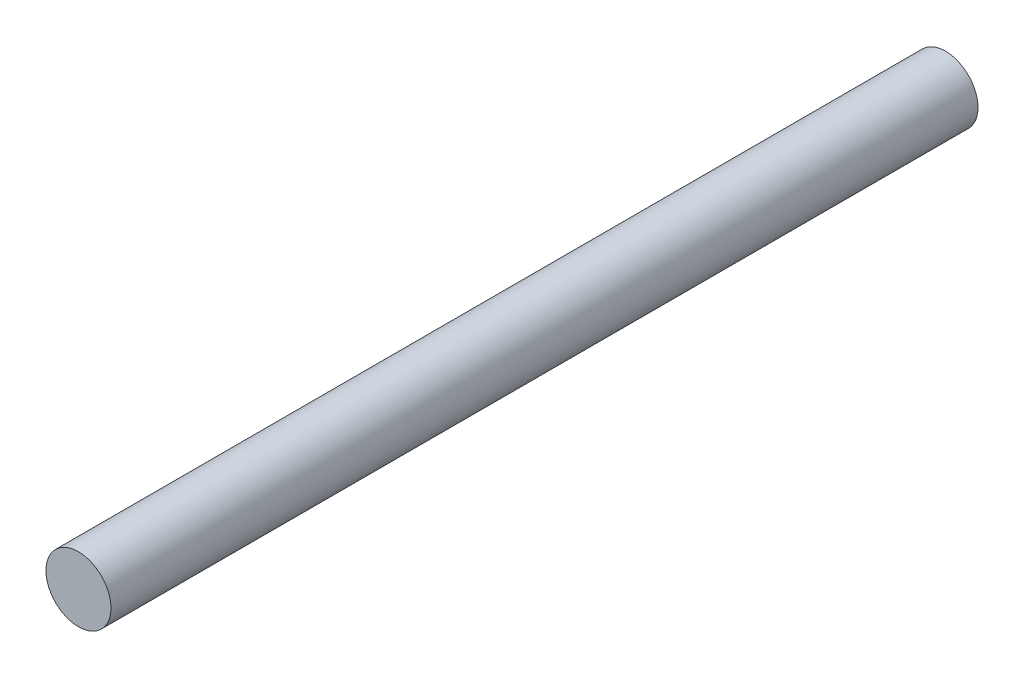
SolidWorks part; units mm, degrees
material "AISI 1020 Steel, Cold Rolled"
ref_plane "Front Plane" through (0, 0, 0) normal (0, 0, 1) x (1, 0, 0)
ref_plane "Top Plane" through (0, 0, 0) normal (0, 1, 0) x (1, 0, 0)
ref_plane "Right Plane" through (0, 0, 0) normal (1, 0, 0) x (0, 0, -1)
sketch "Sketch1" plane through (0, 0, 0) normal (0, 0, 1) x (1, 0, 0)
  circle A0 centre (0, 0) radius 3.75
  dimension "D1" = 7.5
extrude "Boss-Extrude1" add sketch "Sketch1" along normal blind 100
